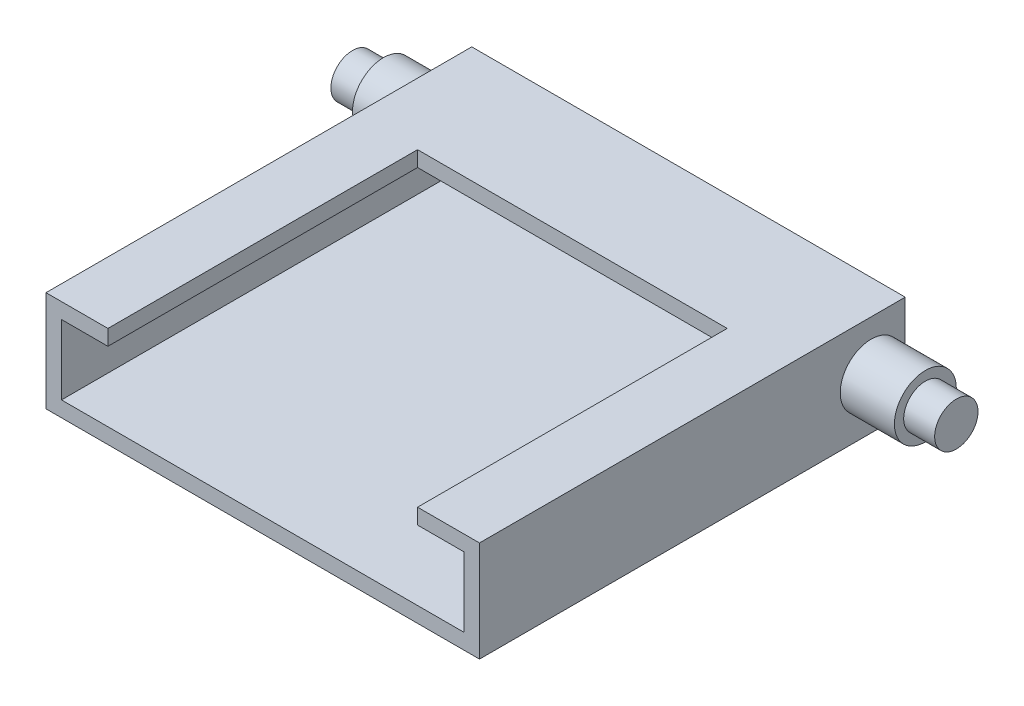
SolidWorks part; units mm, degrees
ref_plane "Front Plane" through (0, 0, 0) normal (0, 0, 1) x (1, 0, 0)
ref_plane "Top Plane" through (0, 0, 0) normal (0, 1, 0) x (1, 0, 0)
ref_plane "Right Plane" through (0, 0, 0) normal (1, 0, 0) x (0, 0, -1)
sketch "Sketch1" plane through (0, 0, 0) normal (0, 1, 0) x (1, 0, 0)
  line L0 (-35.56, 34.925) -> (35.56, -34.925) construction
  line L1 (-35.56, 34.925) -> (35.56, 34.925)
  line L2 (-35.56, 34.925) -> (-35.56, -34.925)
  line L3 (-35.56, -34.925) -> (35.56, -34.925)
  line L4 (35.56, 34.925) -> (35.56, -34.925)
  dimension "D1" = 71.12
  dimension "D2" = 69.85
extrude "Boss-Extrude1" add sketch "Sketch1" along normal blind 16.51 contours L2 L3 L4 L1
sketch "Sketch2" plane through (0, 0, 34.925) normal (0, 0, 1) x (1, 0, 0)
  line L0 (0, 16.51) -> (0, 2.54) construction
  line L1 (-33.02, 13.97) -> (33.02, 13.97)
  line L2 (-33.02, 13.97) -> (-33.02, 2.54)
  line L3 (-33.02, 2.54) -> (33.02, 2.54)
  line L4 (33.02, 13.97) -> (33.02, 2.54)
  line L5 (-35.56, 16.51) -> (35.56, 16.51) construction
  line L6 (-35.56, 8.255) -> (-33.02, 8.255) construction
  line L7 (-35.56, 16.51) -> (-35.56, 0) construction
  dimension "D1" = 66.04
  dimension "D2" = 11.43
shell "Shell1" thickness 2.54
sketch "Sketch3" plane through (35.56, 0, 0) normal (1, 0, 0) x (0, 0, -1)
  line L0 (29.337, 16.51) -> (29.337, 0) construction
  line L2 (34.925, 16.51) -> (-34.925, 16.51) construction
  line L3 (34.925, 0) -> (-34.925, 0) construction
  line L4 (34.925, 16.51) -> (34.925, 0) construction
  circle A0 centre (29.337, 8.255) radius 5.08
  point P8 (34.925, 8.255)
  dimension "D2" = 10.16
  dimension "D1" = 5.588
sketch "Sketch4" plane through (-35.56, 0, 0) normal (-1, 0, 0) x (0, 0, 1)
  line L0 (-29.337, 16.51) -> (-29.337, 0) construction
  circle A0 centre (-29.337, 8.255) radius 5.08
  circle A1 centre (-29.337, 8.255) radius 5.08 construction
extrude "Boss-Extrude2" add sketch "Sketch4" along normal blind 8.89
extrude "Boss-Extrude3" add sketch "Sketch3" along normal blind 8.89 contours A0
sketch "Sketch5" plane through (-44.45, 0, 0) normal (-1, 0, 0) x (0, 0, 1)
  circle A0 centre (-29.337, 8.255) radius 3.556
  dimension "D1" = 7.112
sketch "Sketch6" plane through (44.45, 0, 0) normal (1, 0, 0) x (0, 0, -1)
  circle A0 centre (29.337, 8.255) radius 3.556
  dimension "D1" = 7.112
extrude "Boss-Extrude4" add sketch "Sketch6" along normal blind 5.08
extrude "Boss-Extrude5" add sketch "Sketch5" along normal blind 5.08 contours A0
sketch "Sketch7" plane through (0, 16.51, 0) normal (0, 1, 0) x (1, 0, 0)
  line L0 (-33.02, -34.925) -> (33.02, -34.925) construction
  line L1 (-25.4, -34.925) -> (25.4, -34.925)
  line L2 (-25.4, -34.925) -> (-25.4, 15.875)
  line L3 (-25.4, 15.875) -> (25.4, 15.875)
  line L4 (25.4, -34.925) -> (25.4, 15.875)
  line L5 (0, 0) -> (0, -34.925) construction
  dimension "D1" = 50.8
  dimension "D2" = 50.8
extrude "Cut-Extrude1" cut sketch "Sketch7" against normal up to surface (2.54 mm away) up to face at (0, 13.97, 1.27)
sketch "Sketch8" plane through (0, 0, -34.925) normal (0, 0, -1) x (-1, 0, 0)
  line L0 (0, 11.43) -> (0, 5.08) construction
  line L1 (-12.7, 11.43) -> (12.7, 11.43)
  line L2 (-12.7, 11.43) -> (-12.7, 5.08)
  line L3 (-12.7, 5.08) -> (12.7, 5.08)
  line L4 (12.7, 11.43) -> (12.7, 5.08)
  line L5 (0, 16.51) -> (0, 2.54) construction
  line L7 (-35.56, 8.255) -> (35.56, 8.255) construction
  line L8 (-35.56, 16.51) -> (-35.56, 0) construction
  point P13 (0, 8.255)
  dimension "D1" = 6.35
  dimension "D2" = 25.4
extrude "Cut-Extrude2" cut sketch "Sketch8" against normal up to surface (2.54 mm away) up to face at (0, 8.255, -32.385)
